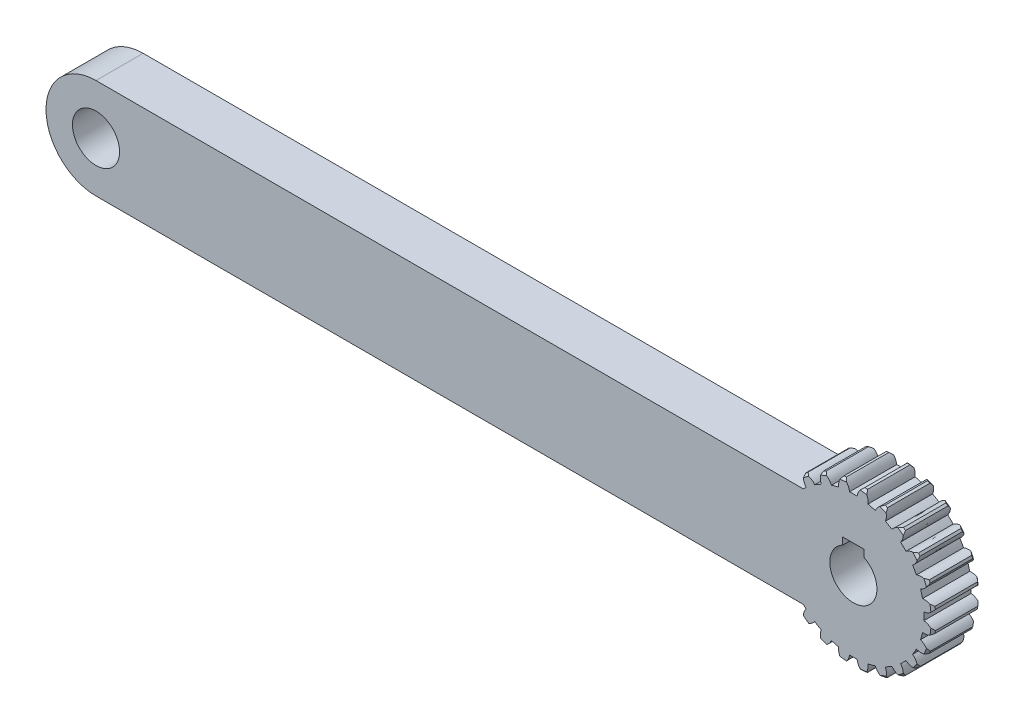
SolidWorks part; units mm, degrees
ref_plane "前视基准面" through (0, 0, 0) normal (0, 0, 1) x (1, 0, 0)
ref_plane "上视基准面" through (0, 0, 0) normal (0, 1, 0) x (1, 0, 0)
ref_plane "右视基准面" through (0, 0, 0) normal (1, 0, 0) x (0, 0, -1)
sketch "草图2" plane through (0, 0, 0) normal (0, 0, 1) x (1, 0, 0)
  circle A1 centre (0, 0) radius 17
extrude "凸台-拉伸2" add sketch "草图2" along normal blind 10
sketch "草图4" plane through (0, 0, 10) normal (0, 0, 1) x (1, 0, 0)
  line L0 (0, 17) -> (0, 0)
  circle A0 centre (0, 0) radius 15
  circle A1 centre (0, 0) radius 17 construction
sketch "草图5" plane through (0, 0, 10) normal (0, 0, 1) x (1, 0, 0)
  line L0 (-1.947, 16.8881) -> (-1.947, 17.5717)
  line L2 (-1.947, 17.5717) -> (1.947, 17.5717)
  line L3 (1.947, 17.5717) -> (1.947, 16.8881)
  circle A0 centre (0, 0) radius 17 construction
  circle A1 centre (0, 0) radius 15 construction
  arc A2 (-0.8, 14.9787) -> (0.8, 14.9787) centre (0, 0) cw
  spline S0 degree 2 poles (-1.947, 16.8881) (-0.9675, 16.1616) (-0.8, 14.9787) knots 0 0 0 1 1 1
  spline S1 degree 2 poles (1.947, 16.8881) (0.9675, 16.1616) (0.8, 14.9787) knots 0 0 0 1 1 1
extrude "切除-拉伸1" cut sketch "草图5" against normal blind 10
pattern_circular "阵列(圆周)1" count 25 every 15 about axis through (0, 0, 10) along (0, 0, -1) of "切除-拉伸1"
sketch "草图6" plane through (0, 0, 10) normal (0, 0, 1) x (1, 0, 0)
  circle A0 centre (0, 0) radius 16.5
extrude "切除-拉伸9" cut sketch "草图6" against normal blind 1 draft 45 flip side to cut
sketch "草图8" plane through (0, 0, 0) normal (0, 0, -1) x (-1, 0, 0)
  circle A0 centre (0, 0) radius 16.5
extrude "切除-拉伸10" cut sketch "草图8" against normal blind 1 draft 45 flip side to cut
sketch "草图11" plane through (0, 0, 10) normal (0, 0, 1) x (1, 0, 0)
  line L1 (-10.6066, 10.6066) -> (-160.6066, 10.6066)
  line L2 (-10.6066, 10.6066) -> (-10.6066, -10.6066)
  line L3 (-10.6066, -10.6066) -> (-160.6066, -10.6066)
  arc A0 (-10.0258, 11.1572) -> (-11.1572, 10.0258) centre (0, 0) ccw construction
  arc A1 (-160.6066, 10.6066) -> (-160.6066, -10.6066) centre (-160.6066, 0) ccw
  dimension "D1" = 150
extrude "凸台-拉伸3" add sketch "草图11" against normal blind 10
sketch "草图13" plane through (0, 0, 0) normal (0, 0, -1) x (-1, 0, 0)
  line L1 (2.25, 4.4651) -> (2.25, 5.9651)
  line L2 (2.25, 5.9651) -> (-2.25, 5.9651)
  line L3 (-2.25, 5.9651) -> (-2.25, 4.4651)
  arc A1 (-2.25, 4.4651) -> (2.25, 4.4651) centre (0, 0) ccw
  dimension "D1" = 4.5
  dimension "D2" = 1.5
  dimension "D3" = 5
extrude "切除-拉伸11" cut sketch "草图13" against normal blind 10
sketch "草图14" plane through (0, 0, 0) normal (0, 0, -1) x (-1, 0, 0)
  circle A0 centre (160.6066, 0) radius 5
extrude "切除-拉伸12" cut sketch "草图14" against normal blind 10
